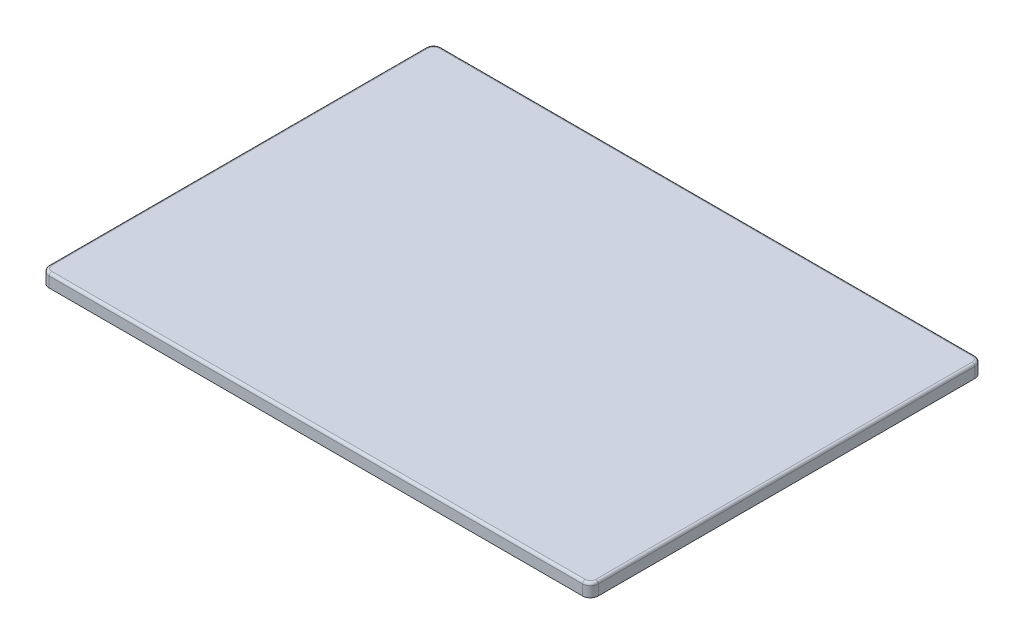
SolidWorks part; units mm, degrees
ref_plane "Front Plane" through (0, 0, 0) normal (0, 0, 1) x (1, 0, 0)
ref_plane "Top Plane" through (0, 0, 0) normal (0, 1, 0) x (1, 0, 0)
ref_plane "Right Plane" through (0, 0, 0) normal (1, 0, 0) x (0, 0, -1)
sketch "Sketch1" plane through (0, 0, 0) normal (0, 1, 0) x (-1, 0, 0)
  line L1 (-2, 5) -> (202, 5)
  line L2 (-5, 2) -> (-5, -142)
  line L3 (-2, -145) -> (202, -145)
  line L4 (205, 2) -> (205, -142)
  arc A0 (-5, -142) -> (-2, -145) centre (-2, -142) ccw
  arc A1 (202, -145) -> (205, -142) centre (202, -142) ccw
  arc A2 (202, 5) -> (205, 2) centre (202, 2) cw
  arc A3 (-2, 5) -> (-5, 2) centre (-2, 2) ccw
  point P10 (-5, -145)
  point P15 (205, 5)
  point P18 (-5, 5)
  dimension "D5" = 3
  dimension "D1" = 210
  dimension "D2" = 150
extrude "Boss-Extrude1" add sketch "Sketch1" along normal blind 5
fillet "Fillet1" radius 1 8 edges at (5, 5, -70) (4.1213, 5, 4.1213) (-100, 5, 5) (-204.1213, 5, 4.1213) (-205, 5, -70) (-204.1213, 5, -144.1213) (-100, 5, -145) (4.1213, 5, -144.1213)
